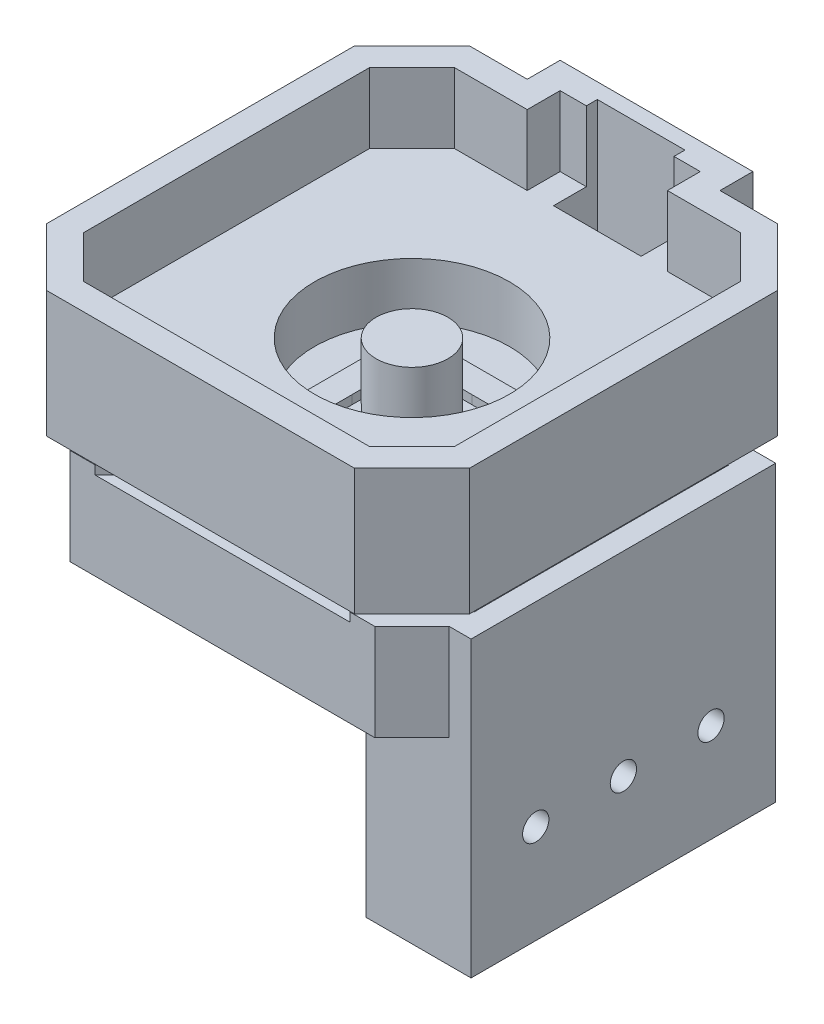
SolidWorks part; units mm, degrees
ref_plane "Front Plane" through (0, 0, 0) normal (0, 0, 1) x (1, 0, 0)
ref_plane "Top Plane" through (0, 0, 0) normal (0, 1, 0) x (1, 0, 0)
ref_plane "Right Plane" through (0, 0, 0) normal (1, 0, 0) x (0, 0, -1)
sketch "Sketch1" plane through (0, 16.3127, 0) normal (0, -1, 0) x (1, 0, 0)
  line L0 (-42.3464, 51.3893) -> (-42.3464, 16.2507)
  line L1 (-42.3464, 16.2507) -> (-35.7657, 9.67)
  line L2 (-35.7657, 9.67) -> (-29.1964, 9.67)
  line L3 (-29.1964, 9.67) -> (-29.1964, 5.92)
  line L4 (-29.1964, 5.92) -> (-7.1964, 5.92)
  line L5 (-7.1964, 5.92) -> (-7.1964, 9.67)
  line L6 (-7.1964, 9.67) -> (-0.6271, 9.67)
  line L7 (-0.6271, 9.67) -> (5.9536, 16.2507)
  line L8 (5.9536, 16.2507) -> (5.9536, 51.3893)
  line L9 (5.9536, 51.3893) -> (-0.6271, 57.97)
  line L10 (-0.6271, 57.97) -> (-35.7657, 57.97)
  line L11 (-35.7657, 57.97) -> (-42.3464, 51.3893)
  line L12 (-10.1964, 12.67) -> (-1.8697, 12.67)
  line L13 (-1.8697, 12.67) -> (2.9536, 17.4933)
  line L14 (2.9536, 17.4933) -> (2.9536, 50.1466)
  line L15 (2.9536, 50.1466) -> (-1.8697, 54.97)
  line L16 (-1.8697, 54.97) -> (-34.5231, 54.97)
  line L17 (-34.5231, 54.97) -> (-39.3464, 50.1466)
  line L18 (-39.3464, 50.1466) -> (-39.3464, 17.4933)
  line L19 (-39.3464, 17.4933) -> (-34.5231, 12.67)
  line L20 (-34.5231, 12.67) -> (-26.1964, 12.67)
  line L21 (-26.1964, 12.67) -> (-26.1964, 8.92)
  line L22 (-26.1964, 8.92) -> (-10.1964, 8.92)
  line L23 (-10.1964, 8.92) -> (-10.1964, 12.67)
  line L24 (-10.1964, 12.67) -> (-1.8697, 12.67)
  line L25 (-1.8697, 12.67) -> (2.9536, 17.4933)
  line L26 (2.9536, 17.4933) -> (2.9536, 50.1466)
  line L27 (2.9536, 50.1466) -> (-1.8697, 54.97)
  line L28 (-1.8697, 54.97) -> (-34.5231, 54.97)
  line L29 (-34.5231, 54.97) -> (-39.3464, 50.1466)
  line L30 (-39.3464, 50.1466) -> (-39.3464, 17.4933)
  line L31 (-39.3464, 17.4933) -> (-34.5231, 12.67)
  line L32 (-34.5231, 12.67) -> (-26.1964, 12.67)
  line L33 (-26.1964, 12.67) -> (-26.1964, 8.92)
  line L34 (-26.1964, 8.92) -> (-10.1964, 8.92)
  line L35 (-10.1964, 8.92) -> (-10.1964, 12.67)
  dimension "D1" = 0
  dimension "D2" = 3
extrude "Boss-Extrude1" add sketch "Sketch1" against normal blind 8
ref_plane "Plane1" through (-35.7657, 16.3127, 57.97) normal (-1, 0, 0) x (0, 0, 1)
sketch "Sketch3" plane through (0, 16.3127, 0) normal (0, -1, 0) x (1, 0, 0)
  line L12 (-35.7657, 57.97) -> (-42.3464, 51.3893)
  line L13 (-42.3464, 51.3893) -> (-42.3464, 16.2507)
  line L14 (-42.3464, 16.2507) -> (-35.7657, 9.67)
  line L15 (-35.7657, 9.67) -> (-29.1964, 9.67)
  line L16 (-29.1964, 9.67) -> (-29.1964, 5.92)
  line L17 (-29.1964, 5.92) -> (-7.1964, 5.92)
  line L18 (-7.1964, 5.92) -> (-7.1964, 9.67)
  line L19 (-7.1964, 9.67) -> (-0.6271, 9.67)
  line L20 (-0.6271, 9.67) -> (5.9536, 16.2507)
  line L21 (5.9536, 16.2507) -> (5.9536, 51.3893)
  line L22 (5.9536, 51.3893) -> (-0.6271, 57.97)
  line L23 (-0.6271, 57.97) -> (-35.7657, 57.97)
  line L24 (-35.7657, 57.97) -> (-42.3464, 51.3893)
  line L25 (-42.3464, 51.3893) -> (-42.3464, 16.2507)
  line L26 (-42.3464, 16.2507) -> (-35.7657, 9.67)
  line L27 (-35.7657, 9.67) -> (-29.1964, 9.67)
  line L28 (-29.1964, 9.67) -> (-29.1964, 5.92)
  line L29 (-29.1964, 5.92) -> (-7.1964, 5.92)
  line L30 (-7.1964, 5.92) -> (-7.1964, 9.67)
  line L31 (-7.1964, 9.67) -> (-0.6271, 9.67)
  line L32 (-0.6271, 9.67) -> (5.9536, 16.2507)
  line L33 (5.9536, 16.2507) -> (5.9536, 51.3893)
  line L34 (5.9536, 51.3893) -> (-0.6271, 57.97)
  line L35 (-0.6271, 57.97) -> (-35.7657, 57.97)
  dimension "D1" = 0
extrude "Boss-Extrude2" add sketch "Sketch3" along normal blind 6.4
sketch "Sketch4" plane through (0, 9.9127, 0) normal (0, -1, 0) x (1, 0, 0)
  line L0 (-39.0561, 54.6796) -> (2.6632, 12.9603) construction
  line L1 (-39.0561, 54.6796) -> (2.6632, 12.9603) construction
  circle A1 centre (-18.1964, 33.82) radius 11.125
  dimension "D1" = 22.25
extrude "Cut-Extrude1" cut sketch "Sketch4" against normal blind 13
sketch "Sketch5" plane through (0, 16.3127, 0) normal (0, -1, 0) x (1, 0, 0)
  circle A0 centre (-18.1964, 33.82) radius 4.1
  dimension "D1" = 8.2
extrude "Boss-Extrude3" add sketch "Sketch5" along normal blind 13 separate body
sketch "Sketch6" plane through (0, 3.3127, 0) normal (0, -1, 0) x (1, 0, 0)
  line L0 (-22.1414, 34.9366) -> (-25.0221, 37.8173)
  line L1 (-33.4551, 46.2503) -> (-34.1622, 45.5432)
  line L2 (-36.9907, 45.5432) -> (-39.8191, 48.3716)
  line L3 (-39.8191, 51.2) -> (-35.5765, 55.4427)
  line L4 (-32.748, 55.4427) -> (-29.9196, 52.6142)
  line L5 (-29.9196, 49.7858) -> (-30.6267, 49.0787)
  line L6 (-30.6267, 49.0787) -> (-25.1964, 43.6484)
  line L7 (-21.0955, 36.7191) -> (-39.0561, 54.6796) construction
  line L8 (-35.5765, 44.129) -> (-34.1622, 56.8569) construction
  line L9 (-18.1964, 33.82) -> (-18.1964, 57.97) construction
  line L10 (-0.6271, 57.97) -> (-35.7657, 57.97) construction
  line L11 (-25.1964, 43.6484) -> (-18.1964, 43.6484)
  line L12 (-18.1964, 43.6484) -> (-18.1964, 40.6484)
  line L13 (-18.1964, 40.6484) -> (-22.1964, 40.6484)
  line L14 (-22.1964, 40.6484) -> (-19.313, 37.765)
  line L15 (-18.1964, 33.82) -> (-42.3464, 33.82) construction
  line L16 (-42.3464, 51.3893) -> (-42.3464, 16.2507) construction
  line L17 (-39.0561, 54.6796) -> (2.6632, 12.9603) construction
  line L18 (-25.1964, 43.6484) -> (-28.0248, 40.82) construction
  line L19 (-22.1964, 40.6484) -> (-25.0221, 37.8173) construction
  line L20 (-28.0248, 40.82) -> (-28.0248, 33.82)
  line L21 (-25.0221, 37.8173) -> (-25.0221, 33.82)
  line L22 (-25.0221, 33.82) -> (-28.0248, 33.82)
  line L23 (-28.0248, 40.82) -> (-33.4551, 46.2503)
  line L24 (-35.5765, 55.4427) -> (-32.748, 55.4427)
  line L25 (-39.8191, 48.3716) -> (-39.8191, 51.2)
  line L26 (-34.1622, 45.5432) -> (-36.9907, 45.5432)
  line L27 (-29.9196, 52.6142) -> (-29.9196, 49.7858)
  circle A0 centre (-34.8694, 50.4929) radius 1.5
  circle A1 centre (-18.1964, 33.82) radius 4.1 construction
  arc A2 (-19.313, 37.765) -> (-22.1414, 34.9366) centre (-18.1964, 33.82) ccw
  arc A3 (-20.0851, 26.1387) -> (-25.8776, 35.7086) centre (-18.1964, 33.82) ccw construction
  point P6 (-41.2333, 49.7858)
  point P8 (-28.5054, 51.2)
  dimension "D5" = 3
  dimension "D9" = 3
  dimension "D1" = 10
  dimension "D2" = 8
  dimension "D3" = 16
  dimension "D4" = 16
  dimension "D6" = 4
  dimension "D7" = 3
  dimension "D8" = 7
extrude "Boss-Extrude4" add sketch "Sketch6" against normal blind 4
pattern_circular "CirPattern2" count 4 over 360 about axis through (-18.1964, 0, 33.82) along (0, 1, 0) of "Boss-Extrude4"
sketch "Sketch7" plane through (0, 24.3127, 0) normal (0, 1, 0) x (1, 0, 0)
  line L0 (-29.1964, -5.92) -> (-7.1964, -5.92) construction
  line L1 (-16.2047, -14.7693) -> (-26.2047, -14.7693)
  line L2 (-16.2047, -14.7693) -> (-16.2047, -5.92)
  line L3 (-16.2047, -5.92) -> (-26.2047, -5.92)
  line L4 (-26.2047, -14.7693) -> (-26.2047, -5.92)
  dimension "D1" = 10
sketch "Sketch8" plane through (0, 24.3127, 0) normal (0, 1, 0) x (1, 0, 0)
  line L7 (-13.1964, -7.67) -> (-13.1964, -12.67)
  line L8 (-13.1964, -12.67) -> (-23.1964, -12.67)
  line L9 (-13.1964, -7.67) -> (-23.1964, -7.67)
  line L10 (-23.1964, -7.67) -> (-23.1964, -12.67)
  line L11 (-34.5231, -12.67) -> (-26.1964, -12.67) construction
  dimension "D2" = 5
extrude "Cut-Extrude2" cut sketch "Sketch8" against normal blind 19
sketch "Sketch9" plane through (0, 3.3127, 0) normal (0, -1, 0) x (1, 0, 0)
  line L0 (-32.748, 12.1973) -> (-3.6448, 12.1973)
  line L1 (3.4263, 19.2683) -> (3.4263, 48.3716)
  line L2 (-3.6448, 55.4427) -> (-32.748, 55.4427)
  line L3 (-39.8191, 48.3716) -> (-39.8191, 19.2683)
  line L48 (-28.0248, 40.82) -> (-28.0248, 26.82)
  line L49 (-28.0248, 26.82) -> (-33.4551, 21.3897)
  line L50 (-33.4551, 21.3897) -> (-34.1622, 22.0968)
  line L51 (-34.1622, 22.0968) -> (-36.9907, 22.0968)
  line L52 (-36.9907, 22.0968) -> (-39.8191, 19.2683)
  line L53 (-39.8191, 19.2683) -> (-39.8191, 16.4399)
  line L54 (-39.8191, 16.4399) -> (-35.5765, 12.1973)
  line L55 (-35.5765, 12.1973) -> (-32.748, 12.1973)
  line L56 (-32.748, 12.1973) -> (-29.9196, 15.0257)
  line L57 (-29.9196, 15.0257) -> (-29.9196, 17.8541)
  line L58 (-29.9196, 17.8541) -> (-30.6267, 18.5612)
  line L59 (-30.6267, 18.5612) -> (-25.1964, 23.9915)
  line L60 (-25.1964, 23.9915) -> (-11.1964, 23.9915)
  line L61 (-11.1964, 23.9915) -> (-5.7661, 18.5612)
  line L62 (-5.7661, 18.5612) -> (-6.4732, 17.8541)
  line L63 (-6.4732, 17.8541) -> (-6.4732, 15.0257)
  line L64 (-6.4732, 15.0257) -> (-3.6448, 12.1973)
  line L65 (-3.6448, 12.1973) -> (-0.8164, 12.1973)
  line L66 (-0.8164, 12.1973) -> (3.4263, 16.4399)
  line L67 (3.4263, 16.4399) -> (3.4263, 19.2683)
  line L68 (3.4263, 19.2683) -> (0.5979, 22.0968)
  line L69 (0.5979, 22.0968) -> (-2.2306, 22.0968)
  line L70 (-2.2306, 22.0968) -> (-2.9377, 21.3897)
  line L71 (-2.9377, 21.3897) -> (-8.368, 26.82)
  line L72 (-8.368, 26.82) -> (-8.368, 40.82)
  line L73 (-8.368, 40.82) -> (-2.9377, 46.2503)
  line L74 (-2.9377, 46.2503) -> (-2.2306, 45.5432)
  line L75 (-2.2306, 45.5432) -> (0.5979, 45.5432)
  line L76 (0.5979, 45.5432) -> (3.4263, 48.3716)
  line L77 (3.4263, 48.3716) -> (3.4263, 51.2)
  line L78 (3.4263, 51.2) -> (-0.8164, 55.4427)
  line L79 (-0.8164, 55.4427) -> (-3.6448, 55.4427)
  line L80 (-3.6448, 55.4427) -> (-6.4732, 52.6142)
  line L81 (-6.4732, 52.6142) -> (-6.4732, 49.7858)
  line L82 (-6.4732, 49.7858) -> (-5.7661, 49.0787)
  line L83 (-5.7661, 49.0787) -> (-11.1964, 43.6484)
  line L84 (-11.1964, 43.6484) -> (-25.1964, 43.6484)
  line L85 (-25.1964, 43.6484) -> (-30.6267, 49.0787)
  line L86 (-30.6267, 49.0787) -> (-29.9196, 49.7858)
  line L87 (-29.9196, 49.7858) -> (-29.9196, 52.6142)
  line L88 (-29.9196, 52.6142) -> (-32.748, 55.4427)
  line L89 (-32.748, 55.4427) -> (-35.5765, 55.4427)
  line L90 (-35.5765, 55.4427) -> (-39.8191, 51.2)
  line L91 (-39.8191, 51.2) -> (-39.8191, 48.3716)
  line L92 (-39.8191, 48.3716) -> (-36.9907, 45.5432)
  line L93 (-36.9907, 45.5432) -> (-34.1622, 45.5432)
  line L94 (-34.1622, 45.5432) -> (-33.4551, 46.2503)
  line L95 (-33.4551, 46.2503) -> (-28.0248, 40.82)
  line L101 (-39.8191, 19.2683) -> (-39.8191, 16.4399)
  line L102 (-39.8191, 16.4399) -> (-35.5765, 12.1973)
  line L103 (-35.5765, 12.1973) -> (-32.748, 12.1973)
  line L113 (-3.6448, 12.1973) -> (-0.8164, 12.1973)
  line L114 (-0.8164, 12.1973) -> (3.4263, 16.4399)
  line L115 (3.4263, 16.4399) -> (3.4263, 19.2683)
  line L125 (3.4263, 48.3716) -> (3.4263, 51.2)
  line L126 (3.4263, 51.2) -> (-0.8164, 55.4427)
  line L127 (-0.8164, 55.4427) -> (-3.6448, 55.4427)
  line L137 (-32.748, 55.4427) -> (-35.5765, 55.4427)
  line L138 (-35.5765, 55.4427) -> (-39.8191, 51.2)
  line L139 (-39.8191, 51.2) -> (-39.8191, 48.3716)
  dimension "D1" = 0
extrude "Boss-Extrude5" add sketch "Sketch9" along normal blind 7 and the other way blind 3
sketch "Sketch10" plane through (3.4263, 0, 0) normal (1, 0, 0) x (0, 0, -1)
  line L1 (-16.4399, -3.6873) -> (-51.2, -3.6873)
  line L2 (-16.4399, -3.6873) -> (-16.4399, 7.3127)
  line L3 (-16.4399, 7.3127) -> (-51.2, 7.3127)
  line L4 (-51.2, -3.6873) -> (-51.2, 7.3127)
extrude "Boss-Extrude6" add sketch "Sketch10" along normal blind 2.5
sketch "Sketch11" plane through (0, -3.6873, 0) normal (0, -1, 0) x (1, 0, 0)
  line L0 (5.9263, 51.2) -> (3.4263, 51.2) construction
  line L1 (5.9263, 16.4399) -> (-6.0737, 16.4399)
  line L2 (5.9263, 16.4399) -> (5.9263, 51.2)
  line L3 (5.9263, 51.2) -> (-6.0737, 51.2)
  line L4 (-6.0737, 16.4399) -> (-6.0737, 51.2)
  dimension "D1" = 12
extrude "Boss-Extrude7" add sketch "Sketch11" along normal blind 22.5
sketch "Sketch12" plane through (-6.0737, 0, 0) normal (-1, 0, 0) x (0, 0, 1)
  line L0 (16.4399, -14.9373) -> (51.2, -14.9373)
  line L1 (16.4399, -26.1873) -> (16.4399, -3.6873) construction
  line L2 (51.2, -26.1873) -> (51.2, -3.6873) construction
  line L3 (33.82, -26.1873) -> (33.82, -3.6873) construction
  line L4 (51.2, -26.1873) -> (16.4399, -26.1873) construction
  line L5 (51.2, -3.6873) -> (16.4399, -3.6873) construction
  circle A0 centre (23.82, -14.9373) radius 1.5
  circle A1 centre (43.82, -14.9373) radius 1.5
  circle A2 centre (33.82, -14.9373) radius 1.5
  dimension "D1" = 10
  dimension "D2" = 10
extrude "Cut-Extrude3" cut sketch "Sketch12" against normal blind 22.5 contours L3 L0 A2 | L0 L3 A2 | A2 L3 L0 | L0 A1 | L0 A0 | L0 A0
